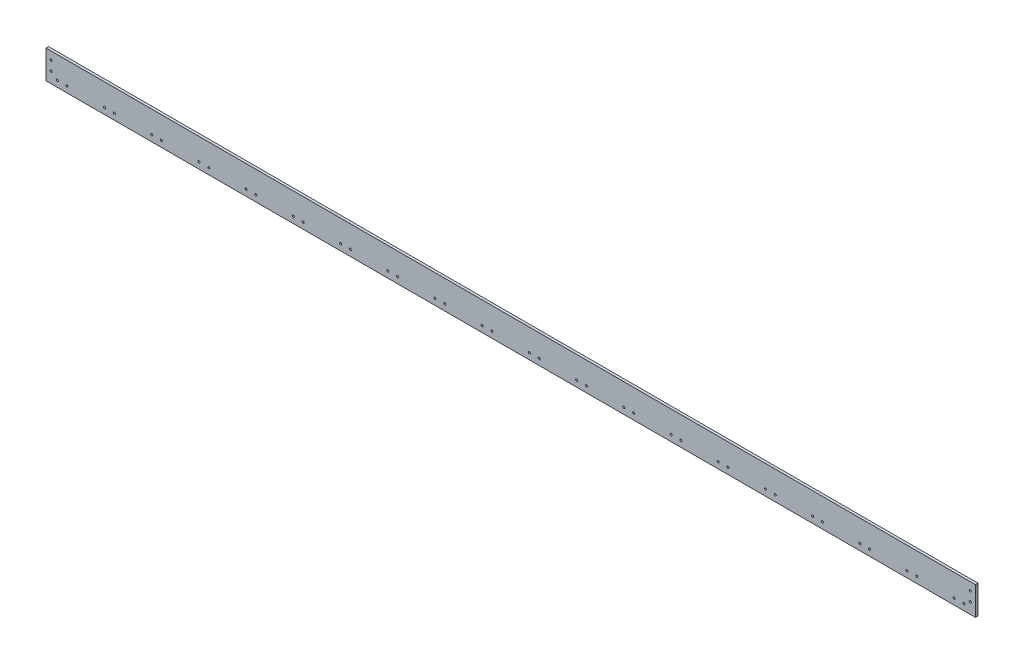
SolidWorks part; units mm, degrees
ref_plane "Front Plane" through (0, 0, 0) normal (0, 0, 1) x (1, 0, 0)
ref_plane "Top Plane" through (0, 0, 0) normal (0, 1, 0) x (1, 0, 0)
ref_plane "Right Plane" through (0, 0, 0) normal (1, 0, 0) x (0, 0, -1)
sketch "Sketch1" plane through (0, 0, 0) normal (0, 0, 1) x (1, 0, 0)
  line L1 (0, 0) -> (2286, 0)
  line L2 (0, 0) -> (0, 69.85)
  line L3 (0, 69.85) -> (2286, 69.85)
  line L4 (2286, 0) -> (2286, 69.85)
  dimension "D1" = 69.85
  dimension "D2" = 2286
extrude "Boss-Extrude1" add sketch "Sketch1" along normal blind 6.35
sketch "Sketch2" plane through (0, 0, 6.35) normal (0, 0, 1) x (1, 0, 0)
  line L0 (27.94, 0) -> (27.94, 12.7) construction
  line L2 (0, 15.24) -> (25.4, 15.24) construction
  line L3 (0, 69.85) -> (0, 0) construction
  line L4 (0, 0) -> (2286, 0) construction
  line L5 (30.48, 15.24) -> (49.53, 15.24) construction
  circle A0 centre (27.94, 15.24) radius 2.54
  circle A1 centre (52.07, 15.24) radius 2.54
  point P13 (1219.2, 76.2)
  dimension "D2" = 5.08
  dimension "D1" = 5.08
  dimension "D3" = 19.05
  dimension "D5" = 12.7
  dimension "D4" = 25.4
extrude "Cut-Extrude1" cut sketch "Sketch2" against normal up to surface (6.35 mm away) contours A1 | A0 up to face at (1143, 34.925, 0)
sketch "Sketch3" plane through (0, 0, 6.35) normal (0, 0, 1) x (1, 0, 0)
  line L0 (0, 69.85) -> (0, 0) construction
  line L1 (2286, 69.85) -> (0, 69.85) construction
  line L2 (12.7, 38.735) -> (0, 38.735) construction
  line L3 (12.7, 48.26) -> (12.7, 29.21) construction
  line L4 (0, 38.735) -> (0, 34.925) construction
  line L5 (1143, 69.85) -> (1143, 0) construction
  line L6 (0, 0) -> (2286, 0) construction
  circle A0 centre (12.7, 26.67) radius 2.54
  circle A1 centre (12.7, 50.8) radius 2.54
  circle A2 centre (2273.3, 26.67) radius 2.54
  circle A3 centre (2273.3, 50.8) radius 2.54
  point P13 (0, 34.925)
  point P15 (1143, 69.85)
  point P17 (12.7, 38.735)
  point P27 (12.7, 38.735)
  dimension "D2" = 5.08
  dimension "D1" = 5.08
  dimension "D3" = 19.05
  dimension "D4" = 12.7
  dimension "D5" = 3.81
extrude "Cut-Extrude2" cut sketch "Sketch3" against normal up to surface (6.35 mm away) up to face at (25.4, 15.24, 0)
pattern_linear "LPattern2" count 20 spacing 116.1047 along (1, 0, 0) of "Cut-Extrude1"
equation "\"vertical-component-width\"= 90in'= \"railing-hypotenuse\" - \"railing-hypotenuse-vertical-component-width-difference\""
equation "\"vertical-component-height\"= 2.75in"
equation "\"material-thickness\"= .25in"
equation "\"D1@Sketch1\"=\"vertical-component-height\""
equation "\"D2@Sketch1\"=\"vertical-component-width\""
equation "\"D1@Boss-Extrude1\"=\"material-thickness\""
equation "\"mounting-hole-diameter\"= .2"
equation "\"mounting-hole-pair-left-to-mount-edge-left\"= 1in"
equation "\"mounting-hole-bottom-to-mount-edge-bottom\"= .5in"
equation "\"mounting-hole-pair-distance-between-holes\"= .75in"
equation "\"distance-between-mounting-hole-pairs\"= ( \"vertical-component-width\" - 2 * \"mounting-hole-pair-left-to-mount-edge-left\" - \"num-mounting-hole-pairs\" * ( 2 * \"mounting-hole-diameter\" + \"mounting-hole-pair-distance-between-holes\" ) ) / ( \"num-mounting-hole-pairs\" - 1 )"
equation "\"num-mounting-hole-pairs\"= 20"
equation "\"D3@Sketch2\"=\"mounting-hole-pair-distance-between-holes\""
equation "\"D5@Sketch2\"=\"mounting-hole-bottom-to-mount-edge-bottom\""
equation "\"D4@Sketch2\"=\"mounting-hole-pair-left-to-mount-edge-left\""
equation "\"D3@LPattern2\"=\"mounting-hole-pair-left-to-next-mounting-hole-pair-left\""
equation "\"D2@Sketch2\"=\"mounting-hole-diameter\""
equation "\"D1@Sketch2\"=\"mounting-hole-diameter\""
equation "\"mounting-hole-pair-left-to-next-mounting-hole-pair-left\"= \"distance-between-mounting-hole-pairs\" + 2 * \"mounting-hole-diameter\" + \"mounting-hole-pair-distance-between-holes\""
equation "\"edge-mounting-hole-pair-inset\"=0.5"
equation "\"D4@Sketch3\"=\"edge-mounting-hole-pair-inset\""
equation "\"edge-mounting-hole-pair-offset-from-mount-vertical-center\"= 0.15"
equation "\"D5@Sketch3\"=\"edge-mounting-hole-pair-offset-from-mount-vertical-center\""
equation "\"D3@Sketch3\"=\"mounting-hole-pair-distance-between-holes\""
equation "\"railing-hypotenuse\"= 92in"
equation "\"railing-hypotenuse-vertical-component-width-difference\"= 1.75in"
equation "\"D1@LPattern2\"=\"num-mounting-hole-pairs\""
